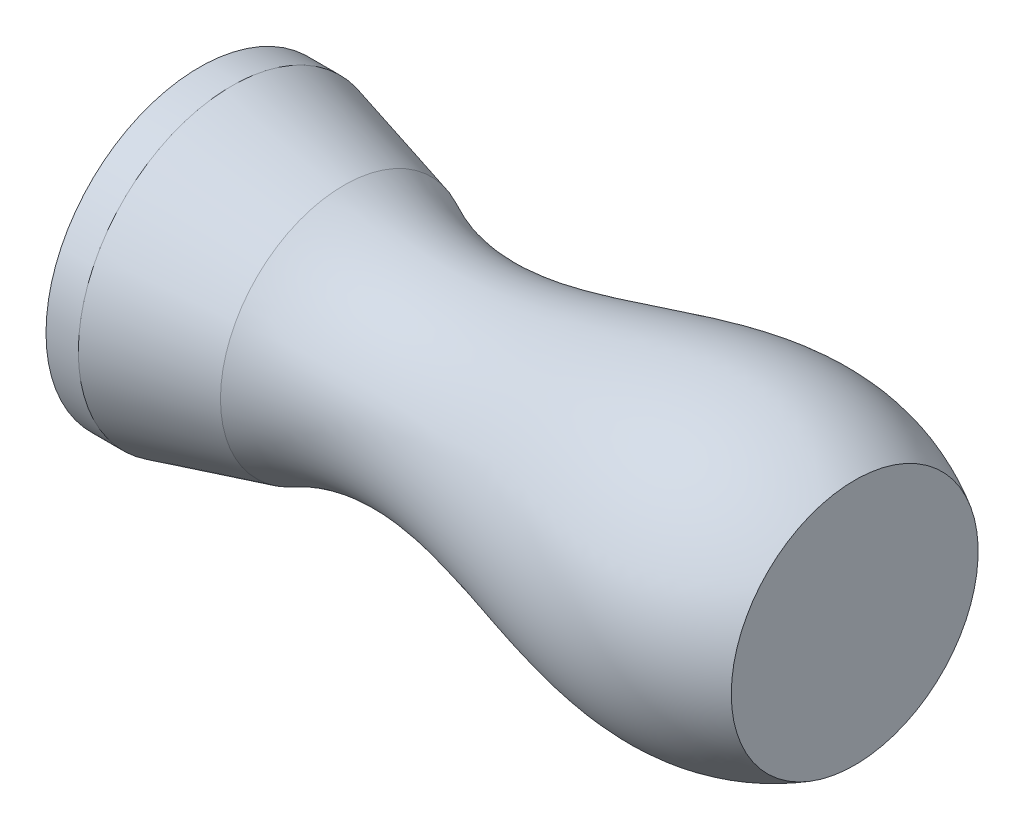
SolidWorks part; units mm, degrees
ref_plane "前基準面" through (0, 0, 0) normal (0, 0, 1) x (1, 0, 0)
ref_plane "上基準面" through (0, 0, 0) normal (0, 1, 0) x (1, 0, 0)
ref_plane "右基準面" through (0, 0, 0) normal (1, 0, 0) x (0, 0, -1)
sketch "草圖1" plane through (0, 0, 0) normal (0, 0, 1) x (1, 0, 0)
  line L0 (0, 0) -> (0, 145.8737)
  line L1 (0, 145.8737) -> (30.7453, 145.8737)
  line L2 (30.7453, 145.8737) -> (137.4822, 117.4106)
  line L3 (0, 0) -> (623.3892, 0)
  line L4 (623.3892, 0) -> (623.3892, 117.4106)
  spline S0 degree 3 poles (137.4822, 117.4106) (298.0666, 35.9624) (457.0501, 212.5415) (623.3892, 117.4106) knots 0 0 0 0 1 1 1 1
  dimension "D1" = 500
revolve "旋轉1" add sketch "草圖1" angle 360 about L3
